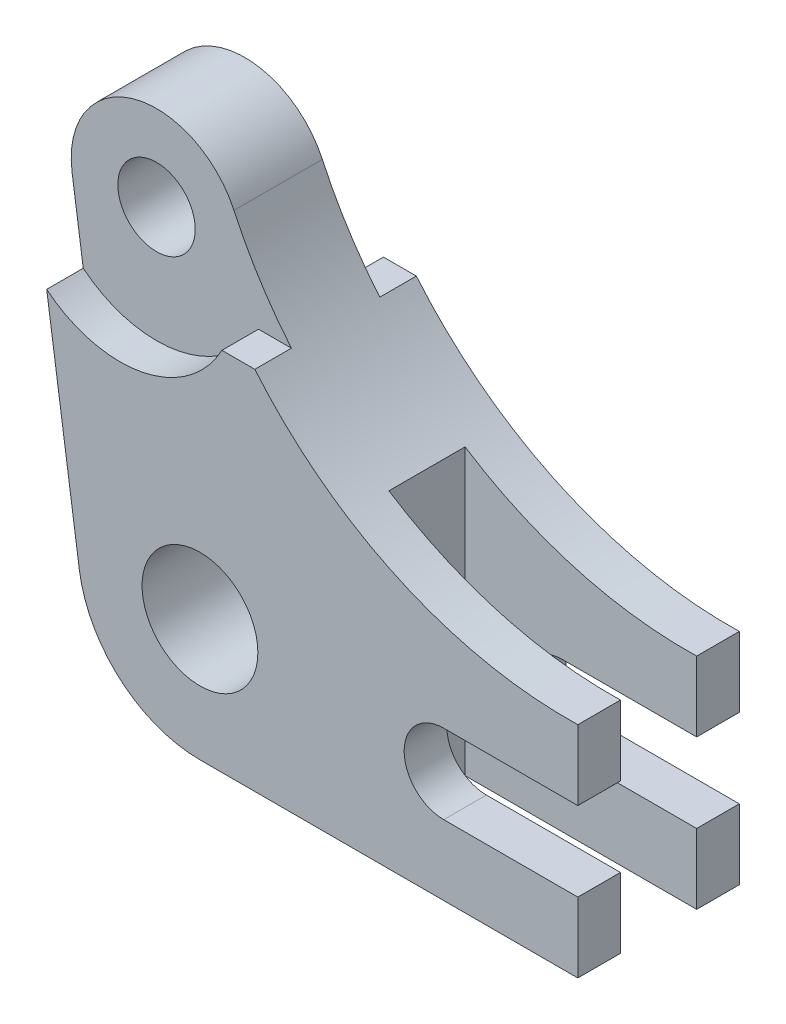
SolidWorks part; units mm, degrees
material "AISI 1020"
ref_plane "Front Plane" through (0, 0, 0) normal (0, 0, 1) x (1, 0, 0)
ref_plane "Top Plane" through (0, 0, 0) normal (0, 1, 0) x (1, 0, 0)
ref_plane "Right Plane" through (0, 0, 0) normal (1, 0, 0) x (0, 0, -1)
sketch "Sketch3" plane through (0, 0, 0) normal (0, 0, 1) x (1, 0, 0)
  line L0 (0, 0) -> (-13.1295, 49) construction
  line L1 (-26.9861, 47.0014) -> (-19.7952, -2.8551)
  line L2 (0, -20) -> (62, -20)
  line L3 (62, -20) -> (62, 16)
  line L4 (62, -2) -> (40, -2) construction
  line L7 (62, -8.5) -> (40, -8.5)
  line L8 (62, 4.5) -> (40, 4.5)
  circle A0 centre (0, 0) radius 9.5
  circle A1 centre (-13.1295, 49) radius 6.35
  circle A2 centre (0, 0) radius 20
  circle A3 centre (-13.1295, 49) radius 14
  arc A4 (-0.421, 54.8732) -> (62, 16) centre (60.398, 82.9808) ccw
  arc A7 (62, -8.5) -> (62, 4.5) centre (62, -2) ccw
  arc A8 (40, 4.5) -> (40, -8.5) centre (40, -2) ccw
  point P16 (51, -2)
  dimension "D1" = 12.7
  dimension "D2" = 19
  dimension "D4" = 40
  dimension "D5" = 28
  dimension "D7" = 67
  dimension "D11" = 22
  dimension "D9" = 6.5
  dimension "D3" = 15
  dimension "D6" = 49
  dimension "D8" = 36
  dimension "D10" = 62
extrude "Boss-Extrude6" add sketch "Sketch3" along normal blind 26.5 contours A8 L8 L3 A4 A3 L1 A2 L2 L7 | A3 A1 | A2 A0
sketch "Sketch7" plane through (0, 0, 0) normal (0, 0, 1) x (1, 0, 0)
  line L1 (62, -20) -> (24, -20)
  line L2 (62, -20) -> (62, 51.1553)
  line L3 (62, 51.1553) -> (24, 51.1553)
  line L4 (24, -20) -> (24, 51.1553)
  dimension "D1" = 38
  dimension "D2" = 71.1553
extrude "Cut-Extrude5" cut sketch "Sketch7" along normal blind 12.5 from offset 7
sketch "Sketch8" plane through (0, 0, 26.5) normal (0, 0, 1) x (1, 0, 0)
  line L0 (-26.9861, 47.0014) -> (-19.7952, -2.8551) construction
  line L1 (3.6037, 40) -> (9.0011, 40)
  arc A0 (-25.1524, 34.2877) -> (3.6037, 40) centre (-13.1295, 49) ccw
  arc A1 (-0.421, 54.8732) -> (62, 16) centre (60.398, 82.9808) ccw construction
  dimension "D1" = 19
  dimension "D2" = 9
extrude "Cut-Extrude6" cut sketch "Sketch8" against normal blind 6 and the other way through all
sketch "Sketch9" plane through (0, 0, 0) normal (0, 0, -1) x (-1, 0, 0)
  line L0 (26.9861, 47.0014) -> (19.7952, -2.8551) construction
  line L1 (-3.6037, 40) -> (-9.0011, 40)
  arc A0 (25.1524, 34.2877) -> (-3.6037, 40) centre (13.1295, 49) cw
  arc A1 (-62, 16) -> (0.421, 54.8732) centre (-60.398, 82.9808) ccw construction
  dimension "D1" = 19
  dimension "D2" = 9
extrude "Cut-Extrude8" cut sketch "Sketch9" against normal blind 6 and the other way through all flip side to cut
equation "\"A\" = 62MM"
equation "\"B\"= 20MM"
equation "\"C\"= 26.5MM"
